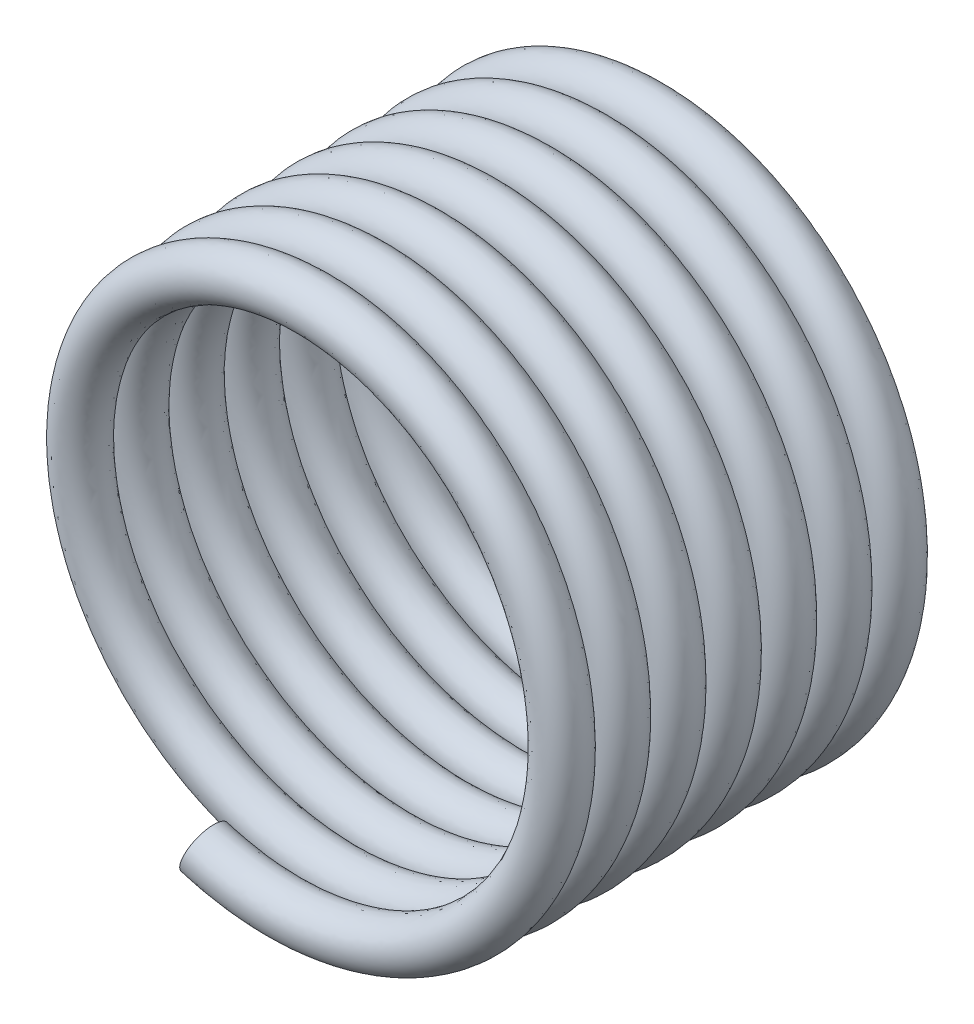
SolidWorks part; units mm, degrees
ref_plane "Front Plane" through (0, 0, 0) normal (0, 0, 1) x (1, 0, 0)
ref_plane "Top Plane" through (0, 0, 0) normal (0, 1, 0) x (1, 0, 0)
ref_plane "Right Plane" through (0, 0, 0) normal (1, 0, 0) x (0, 0, -1)
sketch "Sketch1" plane through (0, 0, 0) normal (0, 0, 1) x (1, 0, 0)
  circle A0 centre (0, 0) radius 5.3721
  dimension "D1" = 10.7442
curve "Helix/Spiral1" pitch 1.1235 height 7.6454 turns 6.805
ref_plane "Plane1" through (-1.8197, -5.0545, 7.6454) normal (-0.9404, 0.3386, 0.0333) x (0.0337, -0.0047, 0.9994)
sketch "Sketch2" plane through (-1.8197, -5.0545, 7.6454) normal (-0.9404, 0.3386, 0.0333) x (0.0337, -0.0047, 0.9994)
  circle A0 centre (0.0016, 0.2066) radius 0.4826
  dimension "D1" = 0.9652
sweep "Sweep1" add profiles "Sketch2" path "Helix/Spiral1"
sketch "Sketch3" plane through (-1.8197, -5.0545, 7.6454) normal (-0.9404, 0.3386, 0.0333) x (0.0337, -0.0047, 0.9994)
  circle A1 centre (0.0016, 0.2066) radius 0.4826
extrude "Boss-Extrude1" [suppressed] add sketch "Sketch3" along normal blind 31.75
sketch "Sketch4" plane through (0, 0, 0) normal (0, -0.9994, -0.0333) x (1, 0, 0)
  circle A0 centre (-5.1654, 0.0001) radius 0.4826
  circle A1 centre (-5.1654, 0.0001) radius 0.4826 construction
extrude "Boss-Extrude2" [suppressed] add sketch "Sketch4" along normal blind 31.75
